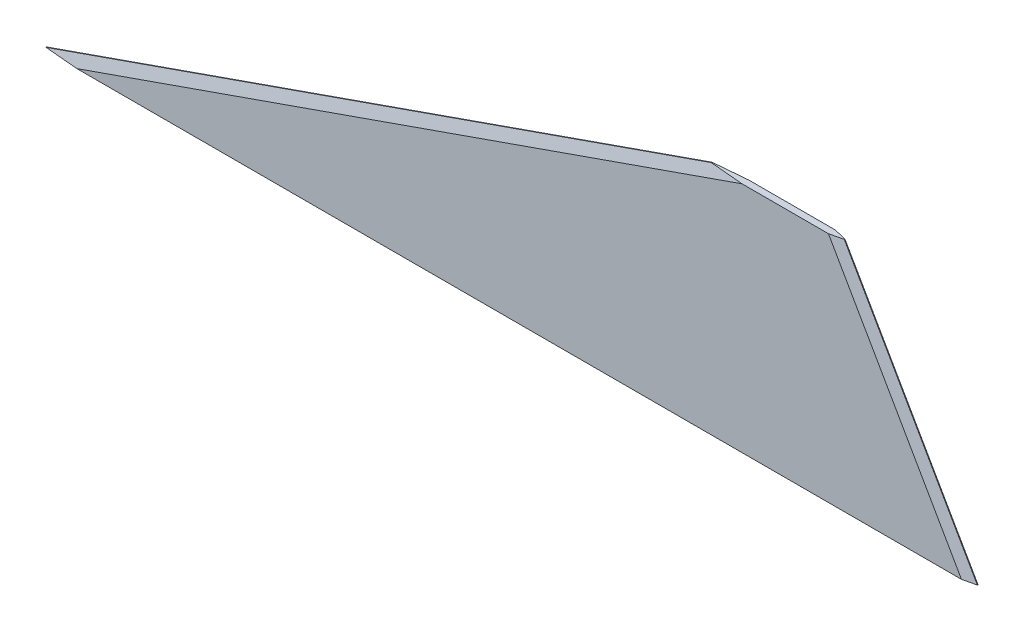
SolidWorks part; units mm, degrees
ref_plane "Front Plane" through (0, 0, 0) normal (0, 0, 1) x (1, 0, 0)
ref_plane "Top Plane" through (0, 0, 0) normal (0, 1, 0) x (1, 0, 0)
ref_plane "Right Plane" through (0, 0, 0) normal (1, 0, 0) x (0, 0, -1)
sketch "Sketch1" plane through (0, 0, 0) normal (0, 0, 1) x (1, 0, 0)
  line L0 (0, 0) -> (355.6, 0)
  line L1 (355.6, 0) -> (304.8, 88.9)
  line L2 (304.8, 88.9) -> (254, 88.9)
  line L3 (254, 88.9) -> (0, 0)
  dimension "D1" = 355.6
  dimension "D2" = 50.8
  dimension "D3" = 50.8
  dimension "D4" = 88.9
extrude "Boss-Extrude1" add sketch "Sketch1" along normal blind 2.54
chamfer "Chamfer2" distance 1.143 angle 75 4 edges at (127, 44.45, 0) (127, 44.45, 2.54) (330.2, 44.45, 2.54) (330.2, 44.45, 0)
